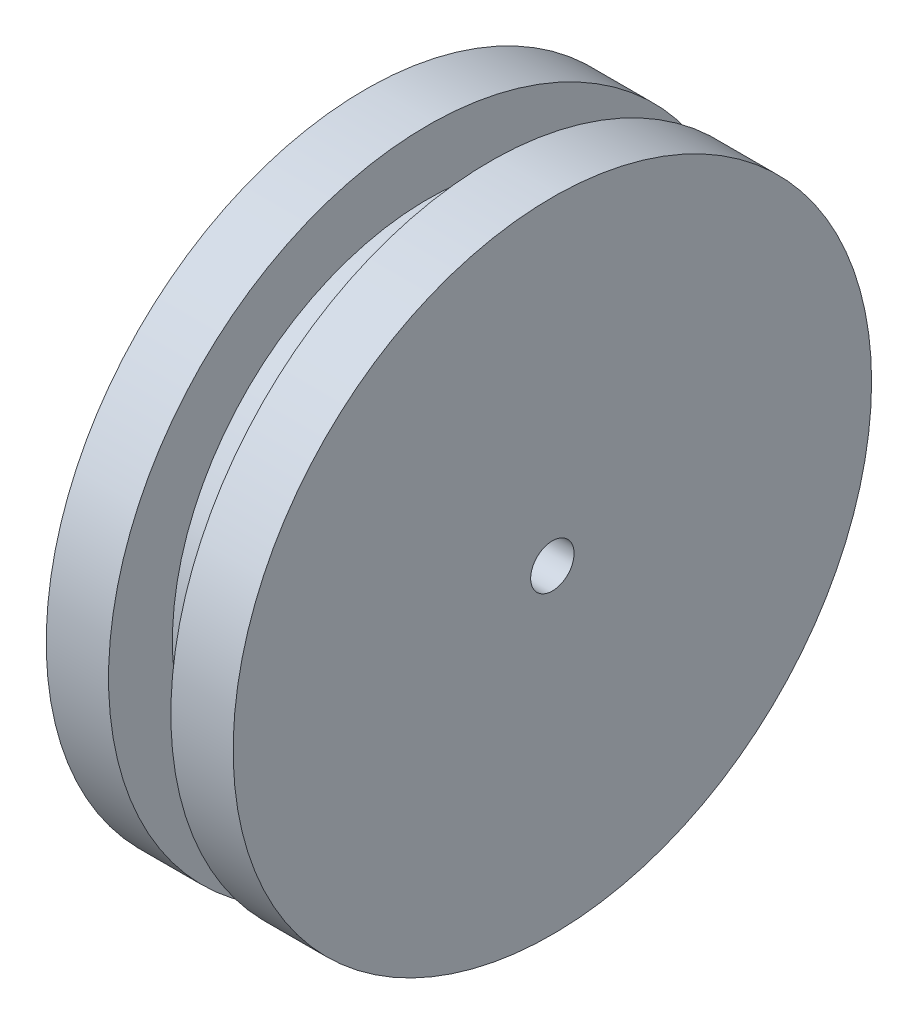
SolidWorks part; units mm, degrees
material "Corrugated Paper"
ref_plane "Front Plane" through (0, 0, 0) normal (0, 0, 1) x (1, 0, 0)
ref_plane "Top Plane" through (0, 0, 0) normal (0, 1, 0) x (1, 0, 0)
ref_plane "Right Plane" through (0, 0, 0) normal (1, 0, 0) x (0, 0, -1)
sketch "Sketch3" plane through (0, 0, 0) normal (1, 0, 0) x (0, 0, -1)
  circle A0 centre (0, 0) radius 15.875
  dimension "D1" = 31.75
extrude "Boss-Extrude1" add sketch "Sketch3" along normal blind 3.0988
sketch "Sketch5" plane through (3.0988, 0, 0) normal (1, 0, 0) x (0, 0, -1)
  circle A0 centre (0, 0) radius 12.7
  dimension "D1" = 25.4
extrude "Boss-Extrude2" add sketch "Sketch5" along normal blind 3.0988 separate body
sketch "Sketch6" plane through (6.1976, 0, 0) normal (1, 0, 0) x (0, 0, -1)
  circle A0 centre (0, 0) radius 15.875 construction
  circle A1 centre (0, 0) radius 15.875
extrude "Boss-Extrude3" add sketch "Sketch6" along normal blind 3.0988 separate body
sketch "Sketch7" plane through (9.2964, 0, 0) normal (1, 0, 0) x (0, 0, -1)
  circle A0 centre (0, 0) radius 1.0795
  dimension "D1" = 2.159
extrude "Cut-Extrude1" cut sketch "Sketch7" against normal through all
equation "\"rodThick\"= 0.085in"
equation "\"thick\"= 0.122in"
equation "\"clear\"= 0.003in"
equation "\"D1@Boss-Extrude2\"=\"thick\""
equation "\"D1@Boss-Extrude1\"=\"thick\""
equation "\"D1@Boss-Extrude3\"=\"thick\""
equation "\"D1@Sketch7\"=\"rodThick\""
